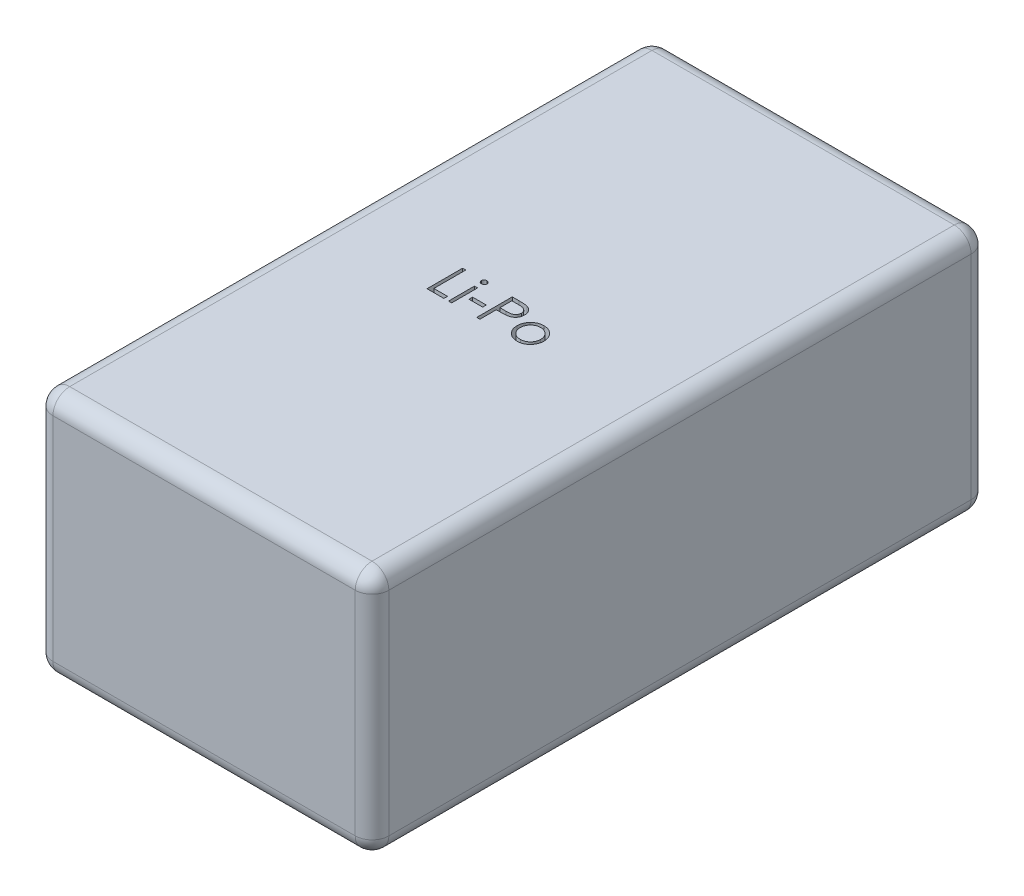
SolidWorks part; units mm, degrees
ref_plane "Front Plane" through (0, 0, 0) normal (0, 0, 1) x (1, 0, 0)
ref_plane "Top Plane" through (0, 0, 0) normal (0, 1, 0) x (1, 0, 0)
ref_plane "Right Plane" through (0, 0, 0) normal (1, 0, 0) x (0, 0, -1)
sketch "Sketch2" plane through (0, 0, 0) normal (0, 0, 1) x (1, 0, 0)
  line L1 (0, 0) -> (30, 0)
  line L2 (0, 0) -> (0, 22)
  line L3 (0, 22) -> (30, 22)
  line L4 (30, 0) -> (30, 22)
  dimension "D1" = 22
  dimension "D2" = 30
extrude "Boss-Extrude1" add sketch "Sketch2" against normal blind 55
fillet "Fillet1" radius 1.5 12 edges at (0, 11, -55) (30, 11, -55) (30, 11, 0) (0, 11, 0) (15, 0, -55) (30, 0, -27.5) (15, 0, 0) (0, 0, -27.5) (0, 22, -27.5) (15, 22, -55) (30, 22, -27.5) (15, 22, 0)
sketch "Sketch3" plane through (0, 22, 0) normal (0, 1, 0) x (1, 0, 0)
  text T0 "Li-Po"
extrude "Cut-Extrude1" cut sketch "Sketch3" against normal blind 10
sketch "Sketch4" plane through (0, 0, 0) normal (0, -1, 0) x (1, 0, 0)
  text T0 "Li-Po"
extrude "Cut-Extrude2" cut sketch "Sketch4" against normal blind 10
